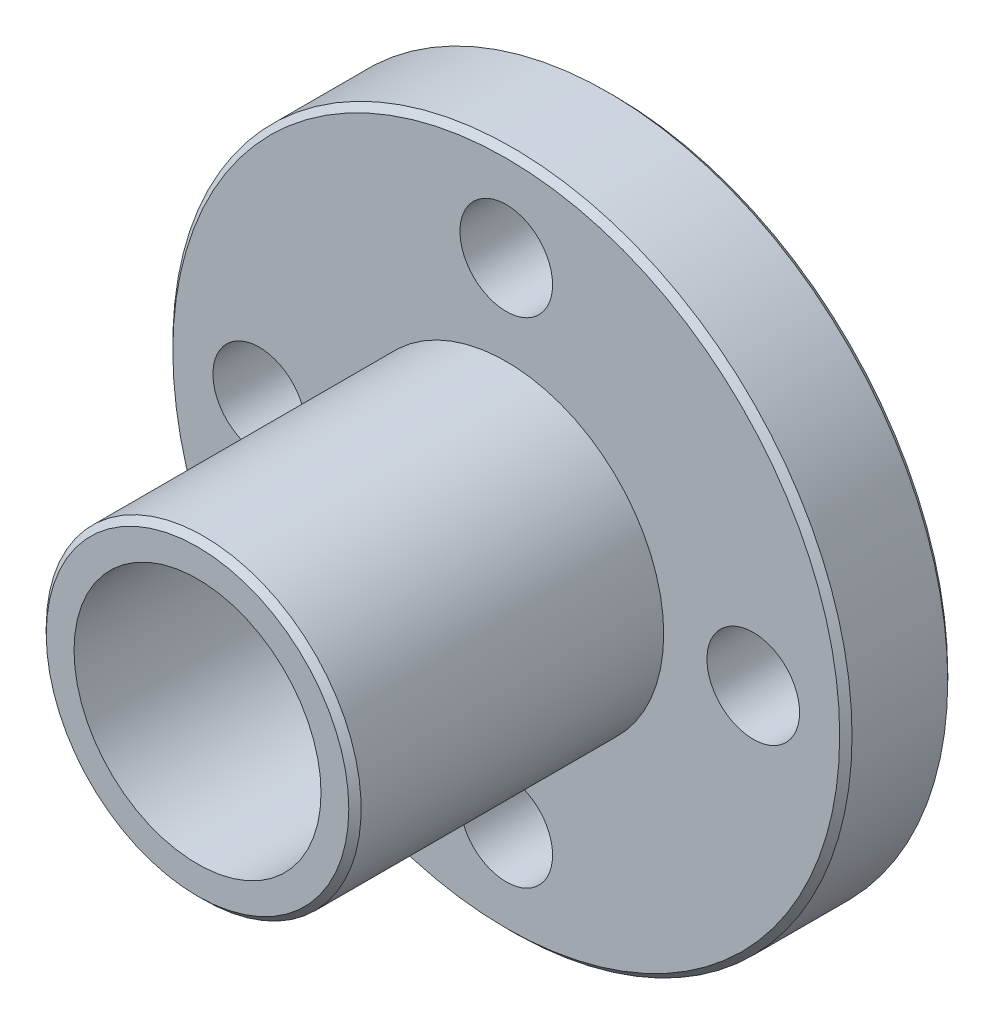
SolidWorks part; units mm, degrees
ref_plane "Front Plane" through (0, 0, 0) normal (0, 0, 1) x (1, 0, 0)
ref_plane "Top Plane" through (0, 0, 0) normal (0, 1, 0) x (1, 0, 0)
ref_plane "Right Plane" through (0, 0, 0) normal (1, 0, 0) x (0, 0, -1)
sketch "Sketch1" plane through (0, 0, 0) normal (0, 0, 1) x (1, 0, 0)
  circle A0 centre (0, 0) radius 5.1
  circle A1 centre (0, 0) radius 4
  dimension "D1" = 10.2
  dimension "D2" = 8
extrude "Boss-Extrude1" add sketch "Sketch1" along normal blind 1.5
sketch "Sketch2" plane through (0, 0, 1.5) normal (0, 0, 1) x (1, 0, 0)
  circle A0 centre (0, 0) radius 11
  circle A1 centre (0, 0) radius 4
  dimension "D1" = 22
  dimension "D2" = 8
extrude "Boss-Extrude2" add sketch "Sketch2" along normal blind 3.5
sketch "Sketch3" plane through (0, 0, 0) normal (0, 0, -1) x (-1, 0, 0)
  circle A0 centre (0, 0) radius 4 construction
  circle A1 centre (0, 0) radius 5.1
  circle A2 centre (0, 0) radius 5.1
  circle A3 centre (0, 0) radius 4
  dimension "D1" = 0
extrude "Boss-Extrude3" add sketch "Sketch3" against normal blind 15
sketch "Sketch4" plane through (0, 0, 1.5) normal (0, 0, -1) x (-1, 0, 0)
  circle A0 centre (0, 8) radius 1.5
  circle A1 centre (8, 0) radius 1.5
  circle A2 centre (0, -8) radius 1.5
  circle A3 centre (-8, 0) radius 1.5
  dimension "D1" = 3
  dimension "D2" = 8
  dimension "D3" = 4
extrude "Cut-Extrude1" cut sketch "Sketch4" against normal through all both and the other way through all
chamfer "Chamfer1" distance 0.2 angle 45 4 edges at (5.1, 0, 0) (11, 0, 1.5) (11, 0, 5) (-5.1, 0, 15)
